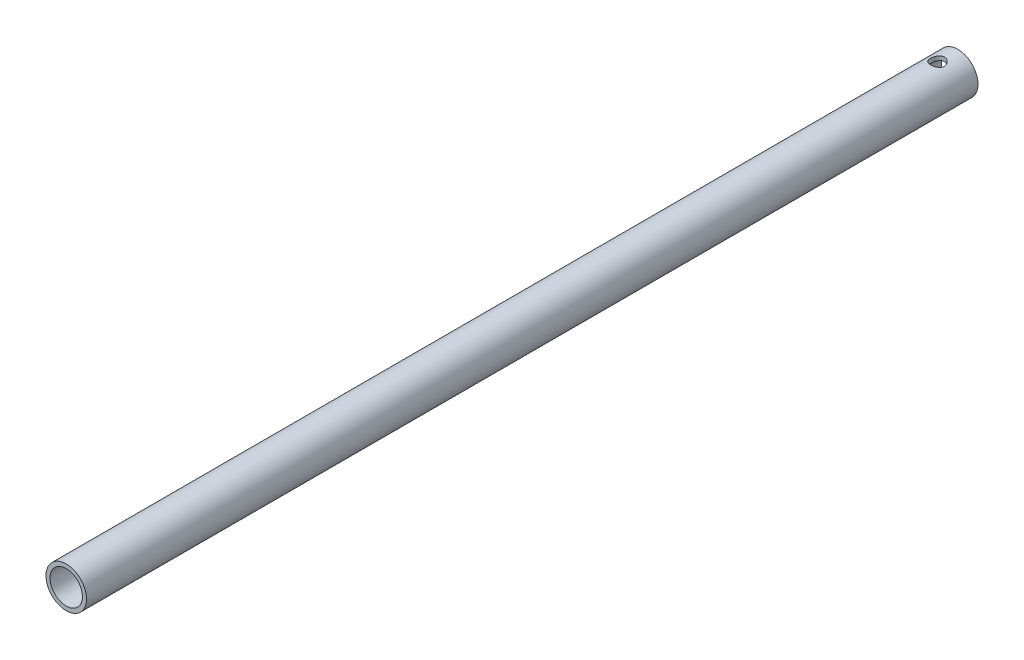
SolidWorks part; units mm, degrees
ref_plane "前视基准面" through (0, 0, 0) normal (0, 0, 1) x (1, 0, 0)
ref_plane "上视基准面" through (0, 0, 0) normal (0, 1, 0) x (1, 0, 0)
ref_plane "右视基准面" through (0, 0, 0) normal (1, 0, 0) x (0, 0, -1)
sketch "草图1" plane through (0, 0, 0) normal (0, 0, 1) x (1, 0, 0)
  circle A0 centre (0, 0) radius 4
  circle A1 centre (0, 0) radius 5
  dimension "D1" = 8
  dimension "D2" = 10
extrude "拉伸1" add sketch "草图1" along normal blind 220
sketch "草图2" plane through (0, 0, 0) normal (0, 1, 0) x (1, 0, 0)
  line L0 (0, -212) -> (0, 49000) construction
  line L1 (-5, -220) -> (5, -220) construction
  line L2 (-2, -210) -> (-2, -20)
  line L3 (2, -210) -> (2, -20)
  line L4 (5, 0) -> (-5, 0) construction
  arc A0 (2, -20) -> (-2, -20) centre (0, -20) ccw
  arc A1 (-2, -210) -> (2, -210) centre (0, -210) ccw
  circle A2 centre (0, -5) radius 1.7
  dimension "D3" = 4
  dimension "D4" = 4
  dimension "D5" = 3.4
  dimension "D1" = 190
  dimension "D2" = 10
  dimension "D6" = 5
extrude "切除-拉伸1" cut sketch "草图2" against normal blind 10
sketch "草图3" plane through (0, 0, 0) normal (0, 1, 0) x (1, 0, 0)
  circle A0 centre (0, -5) radius 1.7 construction
  circle A1 centre (0, -5) radius 1.7
extrude "切除-拉伸3" cut sketch "草图3" along normal blind 16
